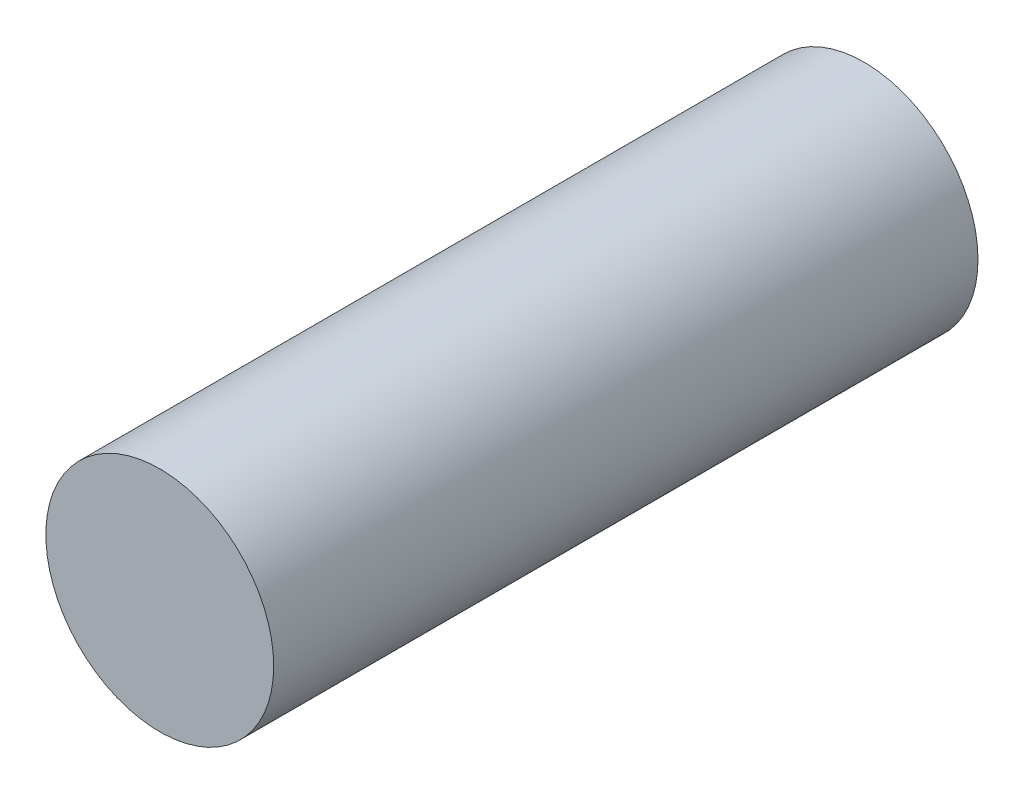
SolidWorks part; units mm, degrees
ref_plane "Front Plane" through (0, 0, 0) normal (0, 0, 1) x (1, 0, 0)
ref_plane "Top Plane" through (0, 0, 0) normal (0, 1, 0) x (1, 0, 0)
ref_plane "Right Plane" through (0, 0, 0) normal (1, 0, 0) x (0, 0, -1)
sketch "Sketch1" plane through (0, 0, 0) normal (0, 0, 1) x (1, 0, 0)
  circle A0 centre (0, 0) radius 11
  dimension "D1" = 22
extrude "Boss-Extrude1" add sketch "Sketch1" along normal blind 68
